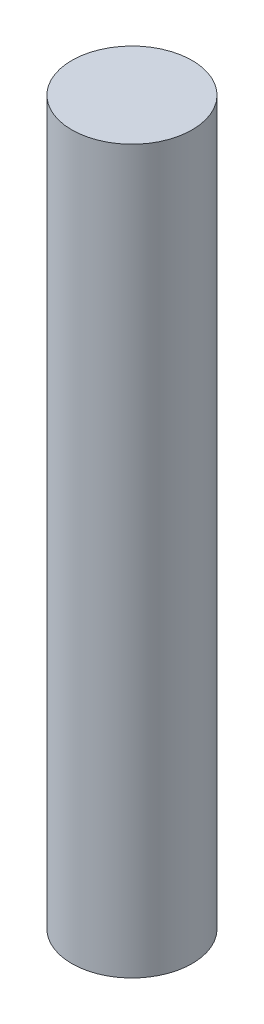
SolidWorks part; units mm, degrees
material "AISI 1020"
ref_plane "Alzado" through (0, 0, 0) normal (0, 0, 1) x (1, 0, 0)
ref_plane "Planta" through (0, 0, 0) normal (0, 1, 0) x (1, 0, 0)
ref_plane "Vista lateral" through (0, 0, 0) normal (1, 0, 0) x (0, 0, -1)
sketch "Croquis1" plane through (0, 0, 0) normal (0, 1, 0) x (1, 0, 0)
  circle A0 centre (0, 0) radius 25
  dimension "D1" = 50
extrude "Saliente-Extruir1" add sketch "Croquis1" along normal blind 300
